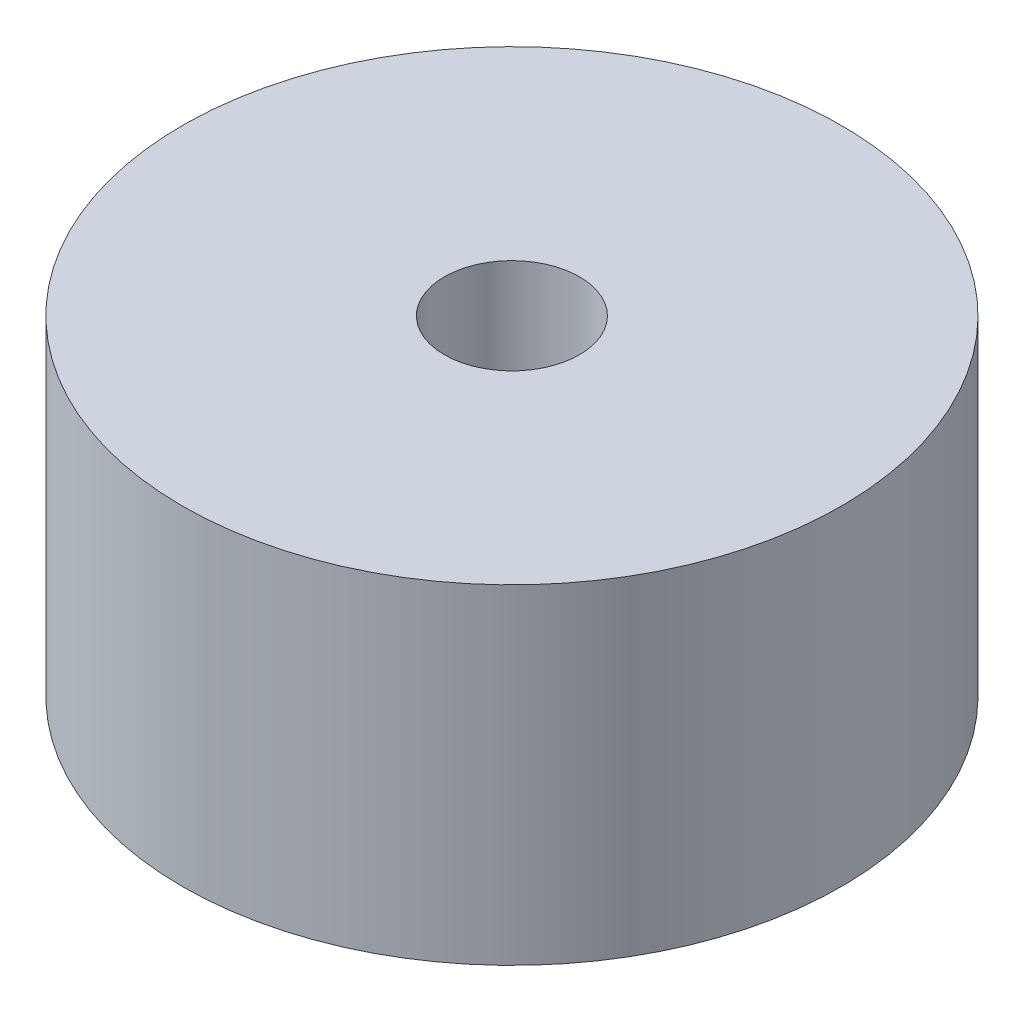
SolidWorks part; units mm, degrees
ref_plane "Front Plane" through (0, 0, 0) normal (0, 0, 1) x (1, 0, 0)
ref_plane "Top Plane" through (0, 0, 0) normal (0, 1, 0) x (1, 0, 0)
ref_plane "Right Plane" through (0, 0, 0) normal (1, 0, 0) x (0, 0, -1)
sketch "Sketch1" plane through (0, 0, 0) normal (0, 1, 0) x (1, 0, 0)
  circle A0 centre (0, 0) radius 5
  dimension "D1" = 10
extrude "Boss-Extrude1" add sketch "Sketch1" along normal blind 5
sketch "Sketch2" plane through (0, 5, 0) normal (0, 1, 0) x (1, 0, 0)
  line L0 (0, 5) -> (0, -5) construction
  circle A0 centre (0, 0) radius 5 construction
hole_wizard "M2.5x0.45 Tapped Hole1" positions "Sketch3" profile "Sketch4" tap size "M2.5x0.45" standard "BSI"
sketch "Sketch3" plane through (0, 5, 0) normal (0, 1, 0) x (1, 0, 0)
  line L0 (0, 5) -> (0, -5) construction
  point P0 (0, 0)
sketch "Sketch4" plane through (0, 5, 0) normal (1, 0, 0) x (0, 0, 1)
  line L0 (0, 0) -> (0, 7.8659)
  line L1 (0, 7.8659) -> (1.025, 7.25)
  line L2 (1.025, 7.25) -> (1.025, 0)
  line L5 (1.025, 0) -> (0, 0)
  line L10 (0, 7.8659) -> (-1.025, 7.25) construction
  line L11 (0, -6.35) -> (0, 107.95) construction
  dimension "Tap Drill Dia." = 2.05
  dimension "Tap Drill Depth" = 7.25
  dimension "Drill Angle" = 118
cosmetic thread "Hole Thread1" parameters "D1"=5, "D2"=2.5
ref_plane "Plane1" through (0, 0, 6) normal (0, 0, 1) x (1, 0, 0)
